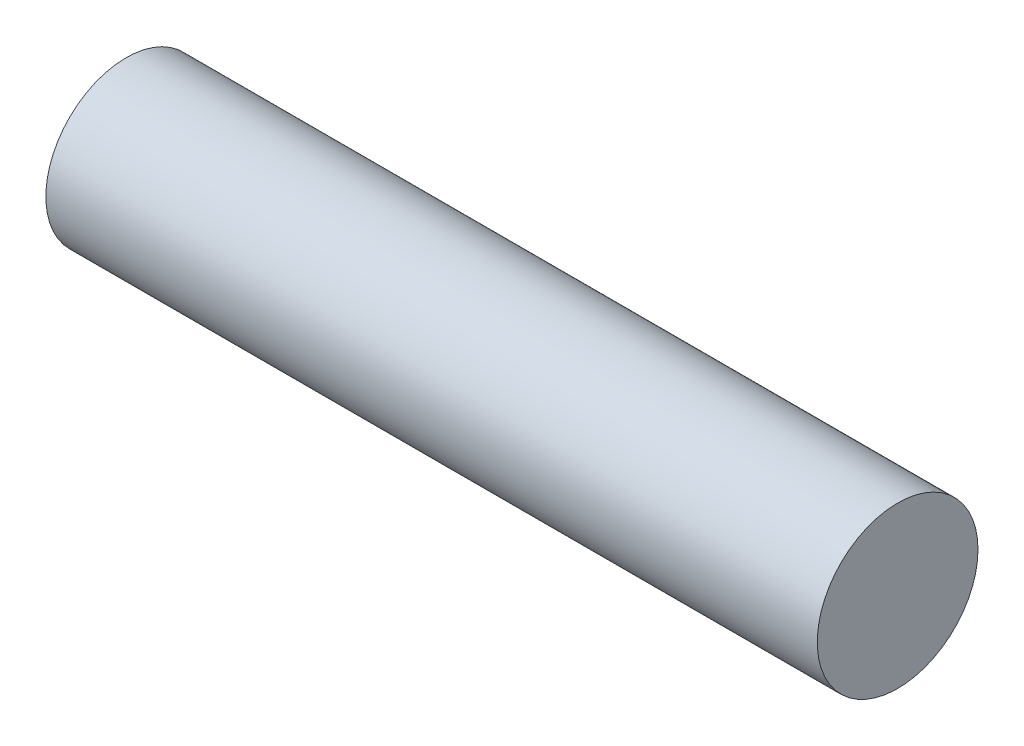
SolidWorks part; units mm, degrees
ref_plane "Front Plane" through (0, 0, 0) normal (0, 0, 1) x (1, 0, 0)
ref_plane "Top Plane" through (0, 0, 0) normal (0, 1, 0) x (1, 0, 0)
ref_plane "Right Plane" through (0, 0, 0) normal (1, 0, 0) x (0, 0, -1)
sketch "Sketch1" plane through (0, 0, 0) normal (1, 0, 0) x (0, 0, -1)
  circle A0 centre (0, 0) radius 2.5
extrude "Boss-Extrude1" add sketch "Sketch1" along normal mid plane 24 contours A0
